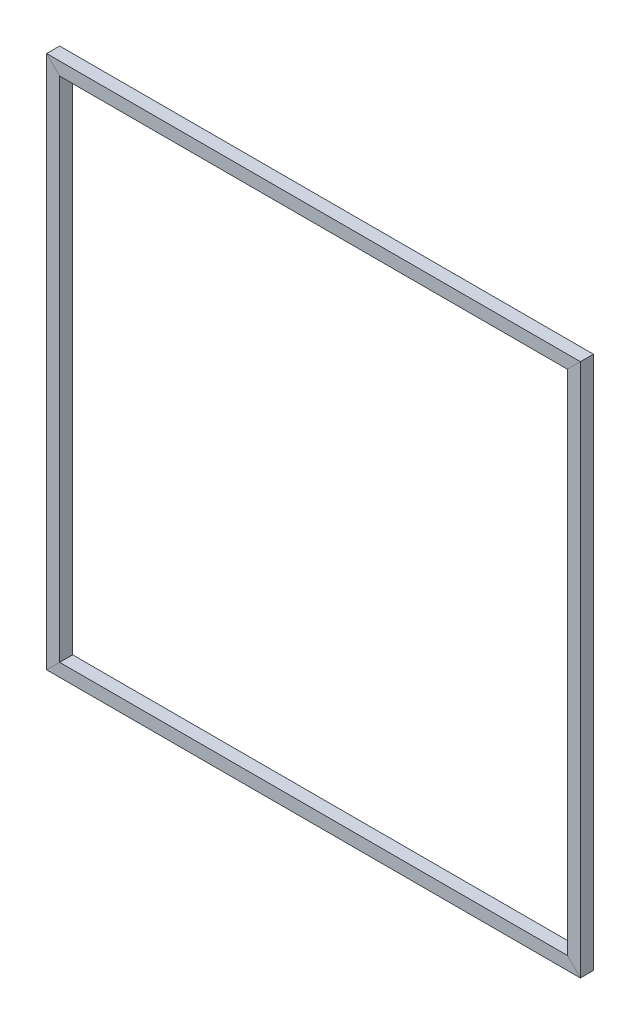
SolidWorks part; units mm, degrees
ref_plane "Front Plane" through (0, 0, 0) normal (0, 0, 1) x (1, 0, 0)
ref_plane "Top Plane" through (0, 0, 0) normal (0, 1, 0) x (1, 0, 0)
ref_plane "Right Plane" through (0, 0, 0) normal (1, 0, 0) x (0, 0, -1)
other "Configuration Table"
sketch "Sketch1" plane through (0, 0, 0) normal (0, 0, 1) x (1, 0, 0)
  line L1 (5000, -5000) -> (-5000, -5000)
  line L2 (5000, -5000) -> (5000, 5000)
  line L3 (5000, 5000) -> (-5000, 5000)
  line L4 (-5000, -5000) -> (-5000, 5000)
  line L5 (5000, -5000) -> (-5000, 5000) construction
  line L6 (5000, 5000) -> (-5000, -5000) construction
  point P0 (0, 0)
  dimension "D1" = 10000
  dimension "D2" = 10000
other "Structural Member1"
ref_plane "Plane1" through (-5000, -5000, 0) normal (0, 1, 0) x (-1, 0, 0)
sketch "Sketch11" plane through (-5000, -5000, 0) normal (0, 1, 0) x (-1, 0, 0)
  line L1 (125, -125) -> (-125, -125)
  line L2 (125, -125) -> (125, 125)
  line L3 (125, 125) -> (-125, 125)
  line L4 (-125, -125) -> (-125, 125)
  line L5 (125, -125) -> (-125, 125) construction
  line L6 (125, 125) -> (-125, -125) construction
  point P0 (0, 0)
  point P2 (0, 0)
  dimension "D2" = 250
  dimension "D1" = 250
